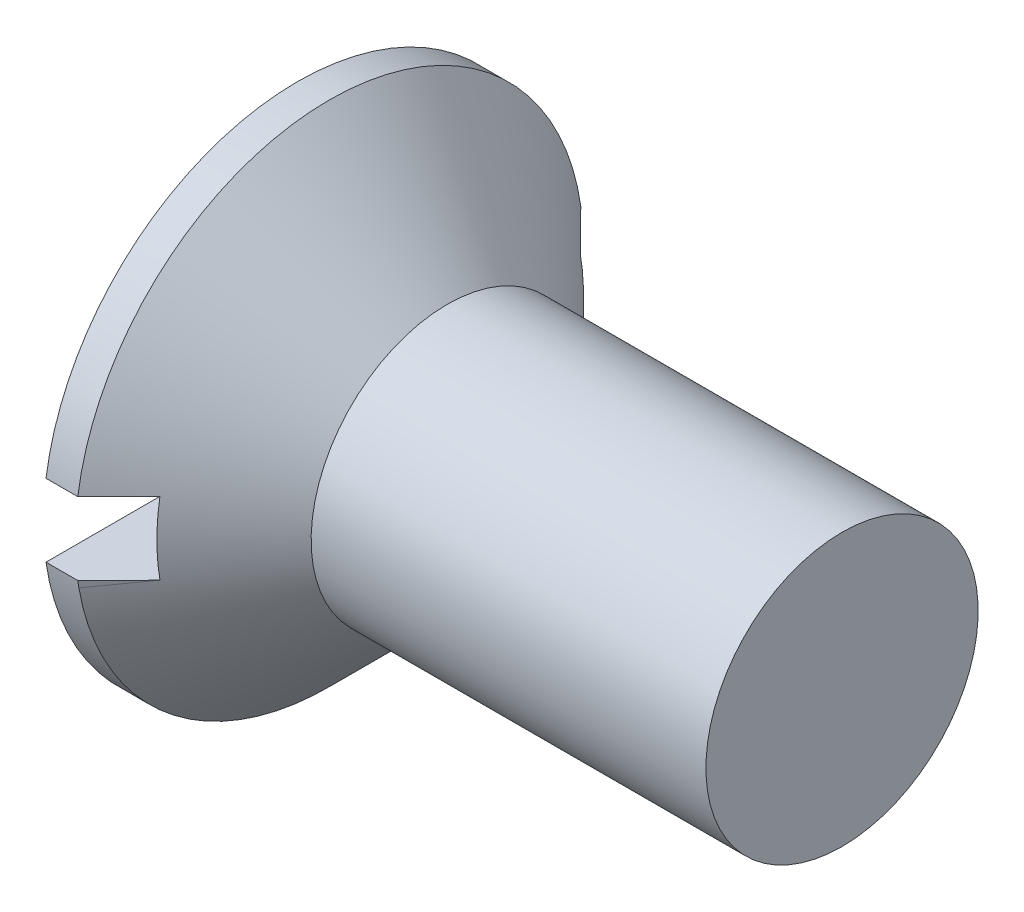
SolidWorks part; units mm, degrees
material "Plain Carbon Steel"
ref_plane "Front Plane" through (0, 0, 0) normal (0, 0, 1) x (1, 0, 0)
ref_plane "Top Plane" through (0, 0, 0) normal (0, 1, 0) x (1, 0, 0)
ref_plane "Right Plane" through (0, 0, 0) normal (1, 0, 0) x (0, 0, -1)
sketch "Sketch1" plane through (0, 0, 0) normal (0, 0, 1) x (1, 0, 0)
  line L0 (0, 0) -> (0, 2.8)
  line L1 (0, 2.8) -> (0.35, 2.8)
  line L2 (0.35, 2.8) -> (1.65, 1.5)
  line L3 (1.65, 1.5) -> (6, 1.5)
  line L4 (6, 1.5) -> (6, 0)
  line L5 (6, 0) -> (0, 0) construction
  line L6 (0, 0) -> (6, 0)
  dimension "D1" = 45
  dimension "D2" = 3
  dimension "D3" = 5.6
  dimension "D4" = 1.65
  dimension "D5" = 6
revolve "Revolve1" add sketch "Sketch1" angle 360 about L5
sketch "Sketch2" plane through (0, 0, 0) normal (-1, 0, 0) x (0, 0, 1)
  line L0 (2.8, 0) -> (-2.8, 0) construction
  line L1 (-2.8, 0.4) -> (2.8, 0.4)
  line L2 (-2.8, 0.4) -> (-2.8, -0.4)
  line L3 (-2.8, -0.4) -> (2.8, -0.4)
  line L4 (2.8, 0.4) -> (2.8, -0.4)
  circle A0 centre (0, 0) radius 2.8 construction
  dimension "D1" = 0.8
extrude "Cut-Extrude1" cut sketch "Sketch2" against normal blind 0.8
